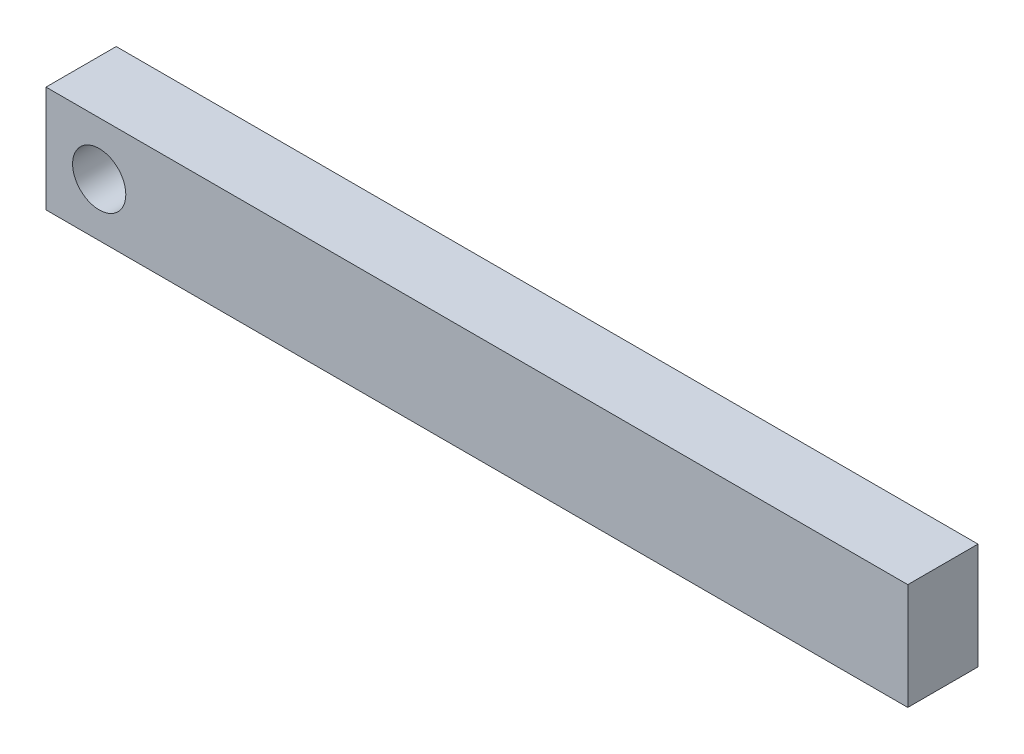
SolidWorks part; units mm, degrees
ref_plane "Front Plane" through (0, 0, 0) normal (0, 0, 1) x (1, 0, 0)
ref_plane "Top Plane" through (0, 0, 0) normal (0, 1, 0) x (1, 0, 0)
ref_plane "Right Plane" through (0, 0, 0) normal (1, 0, 0) x (0, 0, -1)
sketch "Sketch1" plane through (0, 0, 0) normal (0, 0, 1) x (1, 0, 0)
  line L1 (-2.5, 2.5) -> (38, 2.5)
  line L2 (-2.5, 2.5) -> (-2.5, -2.5)
  line L3 (-2.5, -2.5) -> (38, -2.5)
  line L4 (38, 2.5) -> (38, -2.5)
  circle A0 centre (0, 0) radius 1.25
  dimension "D2" = 2.5
  dimension "D3" = 2.5
  dimension "D4" = 2.5
  dimension "D5" = 2.5
extrude "Boss-Extrude1" add sketch "Sketch1" along normal blind 3.3
